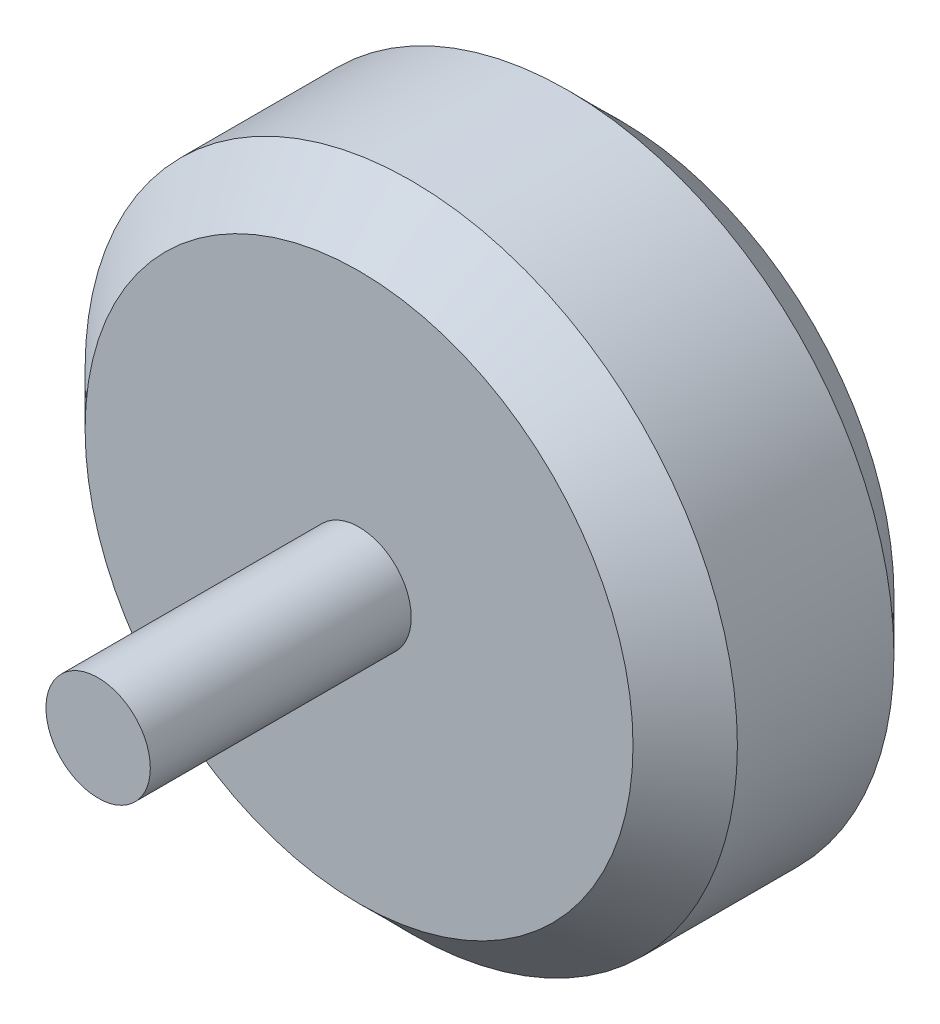
SolidWorks part; units mm, degrees
ref_plane "Front Plane" through (0, 0, 0) normal (0, 0, 1) x (1, 0, 0)
ref_plane "Top Plane" through (0, 0, 0) normal (0, 1, 0) x (1, 0, 0)
ref_plane "Right Plane" through (0, 0, 0) normal (1, 0, 0) x (0, 0, -1)
sketch "Sketch1" plane through (0, 0, 0) normal (0, 0, 1) x (1, 0, 0)
  line L0 (-55.1107, 8) -> (-55.1107, 8.2) construction
  line L1 (-200, 8) -> (0, 8) construction
  line L2 (-55.1107, 8.2) -> (-55.1107, 20.7) construction
  circle A0 centre (-55.1107, 20.7) radius 12.5
  dimension "D2" = 25
  dimension "D1" = 0.2
extrude "Boss-Extrude1" add sketch "Sketch1" along normal mid plane 10
chamfer "Chamfer1" distance 2 angle 45 2 edges at (-42.6107, 20.7, 5) (-42.6107, 20.7, -5)
sketch "Sketch2" plane through (0, 0, 5) normal (0, 0, 1) x (1, 0, 0)
  circle A0 centre (-55.1107, 20.7) radius 2
  dimension "D1" = 4
extrude "Boss-Extrude2" add sketch "Sketch2" along normal blind 10
